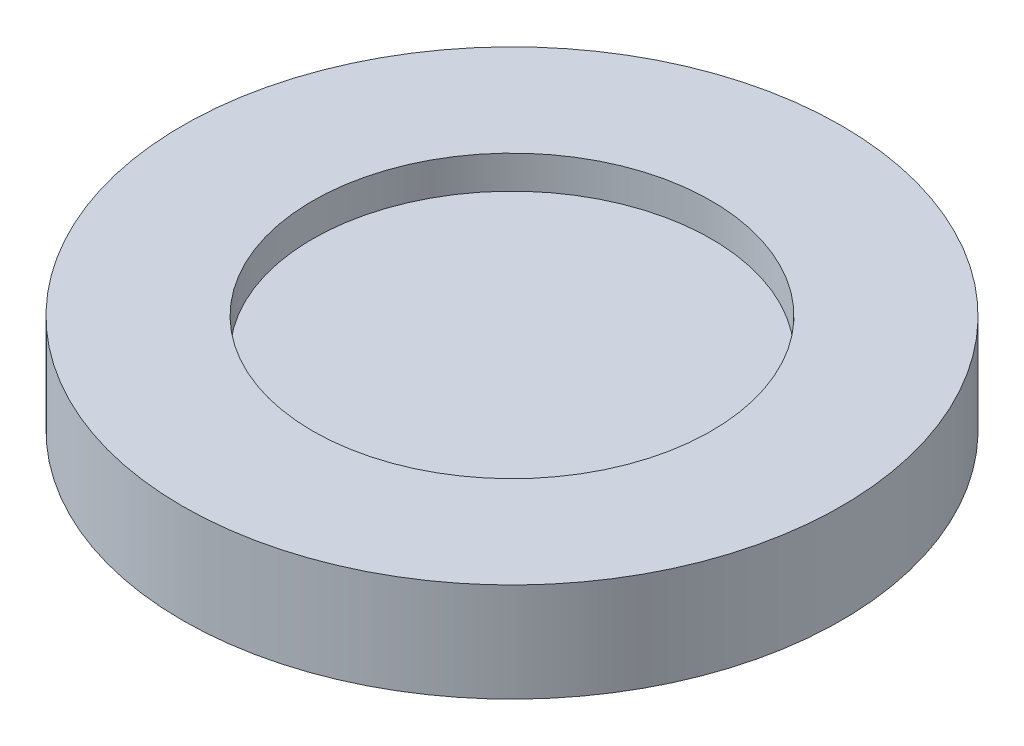
SolidWorks part; units mm, degrees
ref_plane "前视基准面" through (0, 0, 0) normal (0, 0, 1) x (1, 0, 0)
ref_plane "上视基准面" through (0, 0, 0) normal (0, 1, 0) x (1, 0, 0)
ref_plane "右视基准面" through (0, 0, 0) normal (1, 0, 0) x (0, 0, -1)
other "Configuration Table"
sketch "草图1" plane through (0, 0, 0) normal (0, 1, 0) x (1, 0, 0)
  circle A0 centre (0, 0) radius 10
  dimension "D1" = 20
extrude "凸台-拉伸1" add sketch "草图1" along normal blind 3
sketch "草图2" plane through (0, 3, 0) normal (0, 1, 0) x (1, 0, 0)
  circle A0 centre (0, 0) radius 6.05
  dimension "D1" = 12.1
extrude "切除-拉伸1" cut sketch "草图2" against normal blind 1
